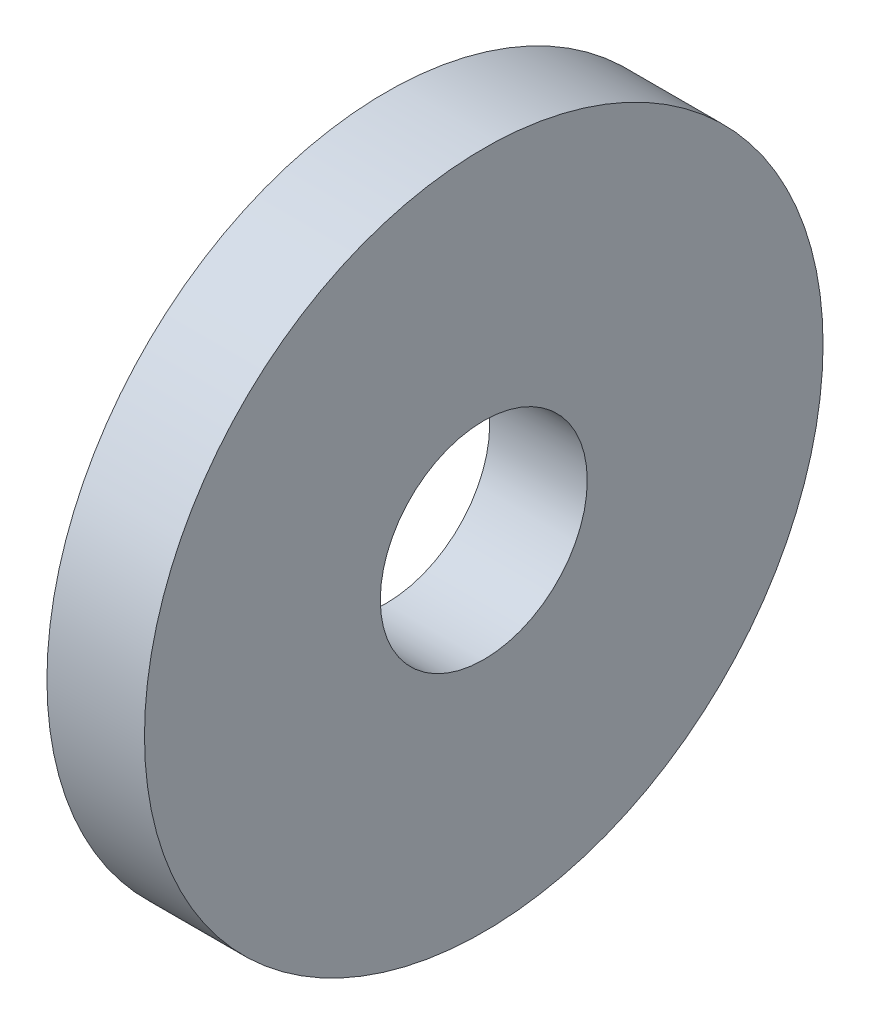
SolidWorks part; units mm, degrees
ref_plane "Plane1" through (0, 0, 0) normal (0, 0, 1) x (1, 0, 0)
ref_plane "Plane2" through (0, 0, 0) normal (0, 1, 0) x (1, 0, 0)
ref_plane "Plane3" through (0, 0, 0) normal (1, 0, 0) x (0, 0, -1)
sketch "Sketch1" plane through (0, 0, 0) normal (0, 0, 1) x (1, 0, 0)
  line L0 (-34.925, 0) -> (9.525, 0) construction
  line L1 (0, 2.44) -> (0, 8)
  line L2 (0, 8) -> (-2.3, 8)
  line L3 (-2.3, 8) -> (-2.3, 2.44)
  line L4 (-2.3, 2.44) -> (0, 2.44)
  dimension "Thickness" = 2.3
  dimension "Inside_dia" = 4.88
  dimension "Outside_dia" = 16
revolve "Base-Revolve" add sketch "Sketch1" angle 360 about L0
